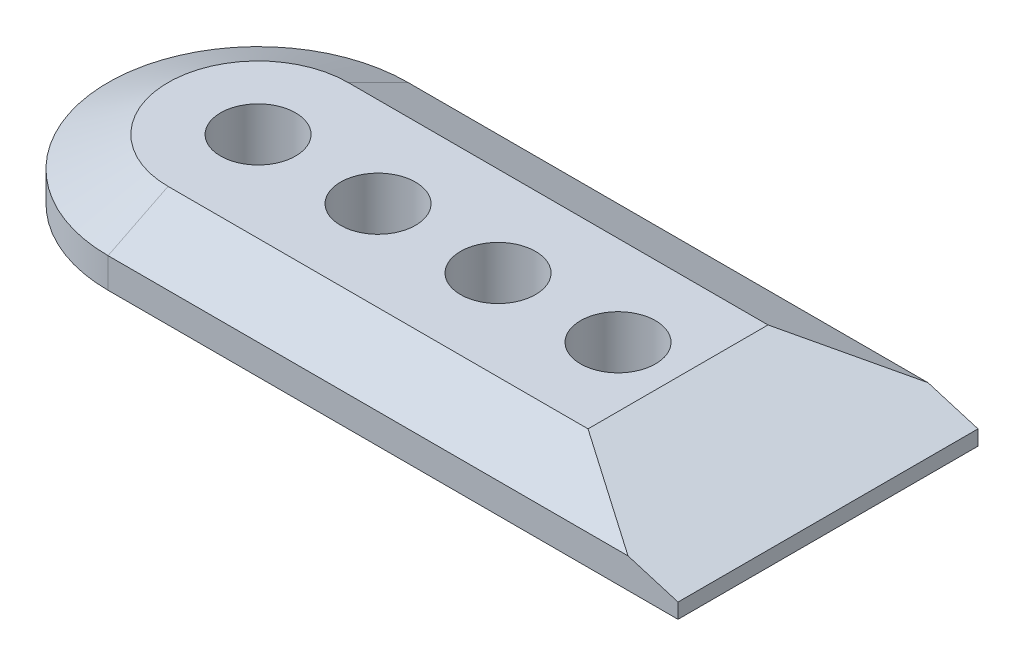
SolidWorks part; units mm, degrees
ref_plane "Front Plane" through (0, 0, 0) normal (0, 0, 1) x (1, 0, 0)
ref_plane "Top Plane" through (0, 0, 0) normal (0, 1, 0) x (1, 0, 0)
ref_plane "Right Plane" through (0, 0, 0) normal (1, 0, 0) x (0, 0, -1)
sketch "Sketch1" plane through (0, 0, 0) normal (0, 1, 0) x (1, 0, 0)
  line L0 (0, -31.75) -> (120.65, -31.75)
  line L1 (120.65, -31.75) -> (120.65, 31.75)
  line L2 (120.65, 31.75) -> (0, 31.75)
  arc A0 (0, -31.75) -> (0, 31.75) centre (0, 0) cw
  point P4 (120.65, 31.75)
  dimension "D1" = 31.75
  dimension "D3" = 63.5
  dimension "D2" = 120.65
extrude "Boss-Extrude1" add sketch "Sketch1" along normal blind 12.7
chamfer "Chamfer1" distance 6.35 distance2 12.7 3 edges at (60.325, 12.7, -31.75) (-31.75, 12.7, 0) (60.325, 12.7, 31.75)
chamfer "Chamfer2" distance 9.525 distance2 31.75 1 edges at (120.65, 12.7, 0)
sketch "Sketch2" plane through (0, 0, 0) normal (0, 1, 0) x (1, 0, 0)
  circle A1 centre (0, 0) radius 7.9375
  circle A2 centre (25.4, 0) radius 7.9375
  circle A3 centre (50.8, 0) radius 7.9375
  circle A4 centre (76.2, 0) radius 7.9375
  point P2 (0, 0)
  dimension "D1" = 15.875
  dimension "D3" = 25.4
  dimension "D2" = 4
extrude "Cut-Extrude3" cut sketch "Sketch2" along normal through all
